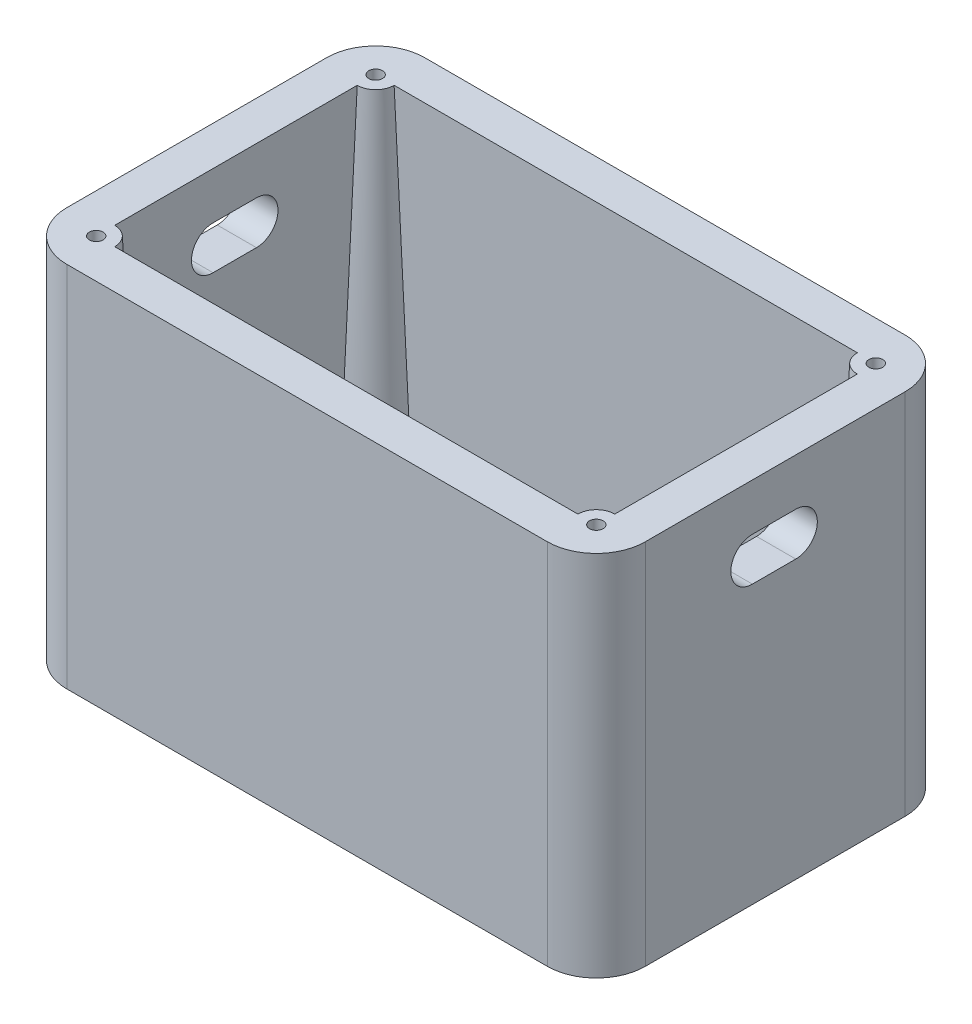
SolidWorks part; units mm, degrees
ref_plane "Front Plane" through (0, 0, 0) normal (0, 0, 1) x (1, 0, 0)
ref_plane "Top Plane" through (0, 0, 0) normal (0, 1, 0) x (1, 0, 0)
ref_plane "Right Plane" through (0, 0, 0) normal (1, 0, 0) x (0, 0, -1)
sketch "Sketch1" plane through (0, 0, 0) normal (0, 1, 0) x (1, 0, 0)
  line L1 (59, -36.5) -> (-59, -36.5)
  line L2 (59, -36.5) -> (59, 36.5)
  line L3 (59, 36.5) -> (-59, 36.5)
  line L4 (-59, -36.5) -> (-59, 36.5)
  line L5 (59, -36.5) -> (-59, 36.5) construction
  line L6 (59, 36.5) -> (-59, -36.5) construction
  point P0 (0, 0)
  dimension "D1" = 118
  dimension "D2" = 73
extrude "Boss-Extrude1" add sketch "Sketch1" along normal blind 75
sketch "Sketch3" plane through (0, 75, 0) normal (0, 1, 0) x (1, 0, 0)
  line L0 (59, -36.5) -> (59, 36.5) construction
  line L1 (-59, -36.5) -> (59, -36.5) construction
  line L2 (-59, 36.5) -> (-59, -36.5) construction
  line L3 (59, 36.5) -> (-59, 36.5) construction
  line L4 (59, -36.5) -> (59, 36.5)
  line L5 (-59, -36.5) -> (59, -36.5)
  line L6 (-59, 36.5) -> (-59, -36.5)
  line L7 (59, 36.5) -> (-59, 36.5)
  line L8 (51, 28.5) -> (-51, 28.5)
  line L9 (-51, 28.5) -> (-51, -28.5)
  line L10 (-51, -28.5) -> (51, -28.5)
  line L11 (51, -28.5) -> (51, 28.5)
  dimension "D1" = 8
extrude "Cut-Extrude2" cut sketch "Sketch3" against normal blind 65 contours L8 L9 L10 L11
fillet "Fillet1" radius 10 4 edges at (-59, 37.5, -36.5) (59, 37.5, -36.5) (-59, 37.5, 36.5) (59, 37.5, 36.5)
sketch "Sketch4" plane through (0, 0, 0) normal (0, -1, 0) x (1, 0, 0)
  line L0 (0, 0) -> (60.9856, 0) construction
  line L1 (0, 0) -> (-59, 0) construction
  line L2 (-59, -26.5) -> (-59, 26.5) construction
  line L3 (-59, 0) -> (-47, 0)
  line L4 (0, 0) -> (0, 36.5) construction
  line L5 (-49, 36.5) -> (49, 36.5) construction
  line L6 (-44.5, 0) -> (-41.5, 0) construction
  line L7 (-44.5, 2.5) -> (-41.5, 2.5)
  line L8 (-44.5, -2.5) -> (-41.5, -2.5)
  line L9 (44.5, 0) -> (41.5, 0) construction
  line L10 (44.5, 2.5) -> (41.5, 2.5)
  line L11 (44.5, -2.5) -> (41.5, -2.5)
  arc A0 (-44.5, 2.5) -> (-44.5, -2.5) centre (-44.5, 0) ccw
  arc A1 (-41.5, -2.5) -> (-41.5, 2.5) centre (-41.5, 0) ccw
  arc A2 (44.5, 2.5) -> (44.5, -2.5) centre (44.5, 0) cw
  arc A3 (41.5, -2.5) -> (41.5, 2.5) centre (41.5, 0) cw
  point P12 (-43, 0)
  point P17 (0, 0)
  point P18 (-47, 0)
  point P21 (43, 0)
  dimension "D2" = 2.5
  dimension "D1" = 12
  dimension "D3" = 3
extrude "Cut-Extrude3" cut sketch "Sketch4" against normal through all contours L8 A1 L7 A0 | A3 L11 A2 L10
sketch "Sketch5" plane through (0, 10, 0) normal (0, 1, 0) x (1, 0, 0)
  line L0 (-59, 0) -> (59, 0) construction
  line L1 (-59, 26.5) -> (-59, -26.5) construction
  line L2 (59, -26.5) -> (59, 26.5) construction
  line L3 (0, 36.5) -> (0, -36.5) construction
  line L4 (49, 36.5) -> (-49, 36.5) construction
  line L5 (-49, -36.5) -> (49, -36.5) construction
  circle A0 centre (-51, 28.5) radius 7.1716
  circle A1 centre (51, 28.5) radius 7.1716
  circle A2 centre (51, -28.5) radius 7.1716
  circle A3 centre (-51, -28.5) radius 7.1716
  dimension "D1" = 14.3431
extrude "Boss-Extrude2" add sketch "Sketch5" along normal up to surface (65 mm away) draft 3 contours A1 | A0 | A3 | A2
sketch "Sketch9" plane through (0, 75, 0) normal (0, 1, 0) x (1, 0, 0)
  line L0 (-51, 24.7349) -> (-51, -24.7349) construction
  line L1 (0, 19.8451) -> (0, 0) construction
  line L2 (0, 0) -> (19.7464, 0) construction
  circle A0 centre (-51, 28.5) radius 1.4
  circle A1 centre (51, 28.5) radius 1.4
  circle A2 centre (51, -28.5) radius 1.4
  circle A3 centre (-51, -28.5) radius 1.4
  dimension "D1" = 2.8
  dimension "D2" = 102
extrude "Cut-Extrude6" cut sketch "Sketch9" against normal blind 5
sketch "Sketch13" plane through (-59, 0, 0) normal (-1, 0, 0) x (0, 0, 1)
  line L0 (0, 0) -> (0, 77.4448) construction
  line L1 (0, 75) -> (0, 61)
  line L2 (-26.5, 75) -> (26.5, 75) construction
  line L3 (-4.1788, 61) -> (4.6705, 61) construction
  line L4 (-4.1788, 65.3999) -> (4.6705, 65.3999)
  line L5 (-4.1788, 56.6001) -> (4.6705, 56.6001)
  arc A0 (-4.1788, 65.3999) -> (-4.1788, 56.6001) centre (-4.1788, 61) ccw
  arc A1 (4.6705, 56.6001) -> (4.6705, 65.3999) centre (4.6705, 61) ccw
  point P9 (0.2458, 61)
  dimension "D1" = 14
extrude "Cut-Extrude7" cut sketch "Sketch13" against normal blind 10000
